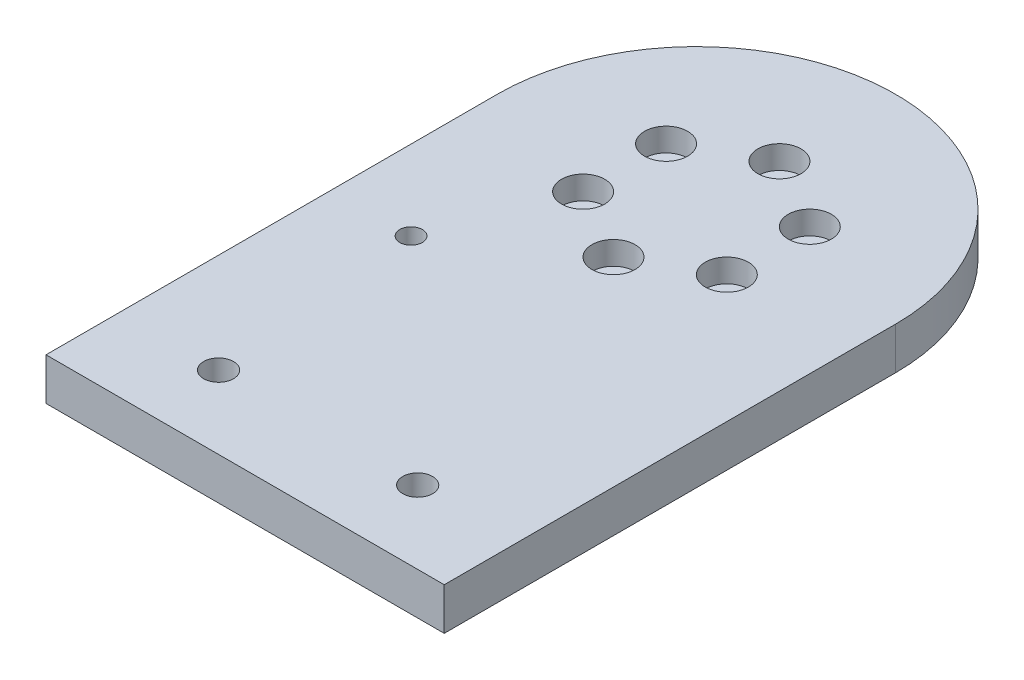
SolidWorks part; units mm, degrees
material "Aleación 6061"
ref_plane "Alzado" through (0, 0, 0) normal (0, 0, 1) x (1, 0, 0)
ref_plane "Planta" through (0, 0, 0) normal (0, 1, 0) x (1, 0, 0)
ref_plane "Vista lateral" through (0, 0, 0) normal (1, 0, 0) x (0, 0, -1)
sketch "Sk_Placa" plane through (0, 0, 0) normal (0, 1, 0) x (1, 0, 0)
  line L1 (-30, -379) -> (30, -379)
  line L2 (-30, -379) -> (-30, -330)
  line L3 (-30, -330) -> (30, -330)
  line L4 (30, -379) -> (30, -330)
  line L5 (-30, -379) -> (30, -330) construction
  line L6 (-30, -330) -> (30, -379) construction
  point P0 (0, -354.5)
  dimension "D1" = 60
  dimension "D2" = 49
  dimension "D3" = 354.5
extrude "Placa" add sketch "Sk_Placa" along normal blind 6.35 from offset 59.75
sketch "Sk_Extremo" plane through (0, 0, 0) normal (0, 1, 0) x (1, 0, 0)
  circle A0 centre (0, -330) radius 30
  dimension "D1" = 60
  dimension "D2" = 330
extrude "Extremo" add sketch "Sk_Extremo" along normal blind 6.35 from offset 59.75
sketch "Sk_Pasantes_M3_cubo_J3" plane through (0, 0, 0) normal (0, 1, 0) x (1, 0, 0)
  circle A0 centre (10.8253, -336.25) radius 1.7
  circle A1 centre (0, -342.5) radius 1.7
  circle A2 centre (-10.8253, -336.25) radius 1.7
  circle A3 centre (-10.8253, -323.75) radius 1.7
  circle A4 centre (0, -317.5) radius 1.7
  circle A5 centre (10.8253, -323.75) radius 1.7
  dimension "D1" = 3.4
  dimension "D4" = 3.4
  dimension "D6" = 3.4
  dimension "D9" = 3.4
  dimension "D12" = 3.4
  dimension "D14" = 3.4
  dimension "D2" = 10.8253
  dimension "D3" = 336.25
  dimension "D5" = 342.5
  dimension "D7" = 10.8253
  dimension "D8" = 336.25
  dimension "D10" = 10.8253
  dimension "D11" = 323.75
  dimension "D13" = 317.5
  dimension "D15" = 10.8253
  dimension "D16" = 323.75
extrude "Pasantes_M3_cubo_J3" cut sketch "Sk_Pasantes_M3_cubo_J3" along normal blind 6.35 from offset 59.75
sketch "Sk_Cajas_M3_J3" plane through (0, 0, 0) normal (0, 1, 0) x (1, 0, 0)
  circle A0 centre (10.8253, -336.25) radius 3.25
  circle A1 centre (0, -342.5) radius 3.25
  circle A2 centre (-10.8253, -336.25) radius 3.25
  circle A3 centre (-10.8253, -323.75) radius 3.25
  circle A4 centre (0, -317.5) radius 3.25
  circle A5 centre (10.8253, -323.75) radius 3.25
  dimension "D1" = 6.5
  dimension "D4" = 6.5
  dimension "D6" = 6.5
  dimension "D9" = 6.5
  dimension "D12" = 6.5
  dimension "D14" = 6.5
  dimension "D2" = 10.8253
  dimension "D3" = 336.25
  dimension "D5" = 342.5
  dimension "D7" = 10.8253
  dimension "D8" = 336.25
  dimension "D10" = 10.8253
  dimension "D11" = 323.75
  dimension "D13" = 317.5
  dimension "D15" = 10.8253
  dimension "D16" = 323.75
extrude "Cajas_M3_J3" cut sketch "Sk_Cajas_M3_J3" along normal blind 3.5 from offset 62.6
sketch "Sk_Extension_pestanas" plane through (0, 0, 0) normal (0, 1, 0) x (1, 0, 0)
  line L1 (-30, -398) -> (30, -398)
  line L2 (-30, -398) -> (-30, -379)
  line L3 (-30, -379) -> (30, -379)
  line L4 (30, -398) -> (30, -379)
  line L5 (-30, -398) -> (30, -379) construction
  line L6 (-30, -379) -> (30, -398) construction
  point P0 (0, -388.5)
  dimension "D1" = 60
  dimension "D2" = 19
  dimension "D3" = 388.5
extrude "Extension_pestanas" add sketch "Sk_Extension_pestanas" along normal blind 6.35 from offset 59.75
sketch "Sk_Pasantes_M4_repisa" plane through (0, 0, 0) normal (0, 1, 0) x (1, 0, 0)
  circle A0 centre (-15, -387) radius 2.25
  circle A1 centre (15, -387) radius 2.25
  dimension "D1" = 4.5
  dimension "D4" = 4.5
  dimension "D2" = 15
  dimension "D3" = 387
  dimension "D5" = 15
  dimension "D6" = 387
extrude "Pasantes_M4_repisa" cut sketch "Sk_Pasantes_M4_repisa" along normal blind 6.35 from offset 59.75
sketch "Sk_Pasante_M3_cincho" plane through (0, 0, 0) normal (0, 1, 0) x (1, 0, 0)
  circle A0 centre (-18, -355) radius 1.7
  dimension "D1" = 3.4
  dimension "D2" = 18
  dimension "D3" = 355
extrude "Pasante_M3_cincho" cut sketch "Sk_Pasante_M3_cincho" along normal blind 6.35 from offset 59.75
